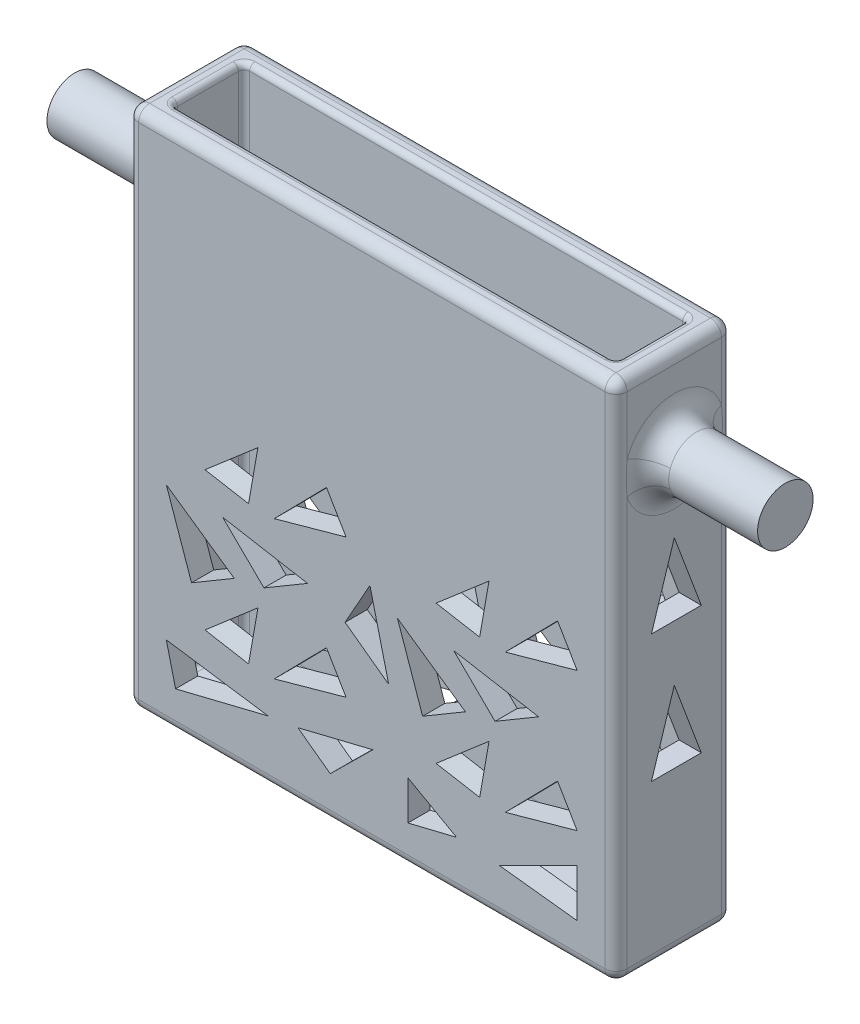
SolidWorks part; units mm, degrees
ref_plane "Front Plane" through (0, 0, 0) normal (0, 0, 1) x (1, 0, 0)
ref_plane "Top Plane" through (0, 0, 0) normal (0, 1, 0) x (1, 0, 0)
ref_plane "Right Plane" through (0, 0, 0) normal (1, 0, 0) x (0, 0, -1)
sketch "Sketch1" plane through (0, 0, 0) normal (0, 1, 0) x (1, 0, 0)
  line L0 (-40, 6.5) -> (-40, -6.5)
  line L1 (-38.5, 5) -> (38.5, 5) construction
  line L2 (-38.5, 5) -> (-38.5, -5) construction
  line L3 (-38.5, -5) -> (38.5, -5) construction
  line L4 (38.5, 5) -> (38.5, -5) construction
  line L5 (-38.5, 5) -> (38.5, -5) construction
  line L6 (-38.5, -5) -> (38.5, 5) construction
  line L7 (-40, -6.5) -> (40, -6.5)
  line L8 (40, 6.5) -> (40, -6.5)
  line L9 (-40, 6.5) -> (40, 6.5)
  line L10 (-44, 10.5) -> (44, 10.5)
  line L11 (44, 10.5) -> (44, -10.5)
  line L12 (-44, -10.5) -> (44, -10.5)
  line L13 (-44, 10.5) -> (-44, -10.5)
  point P0 (0, 0)
  dimension "D1" = 77
  dimension "D2" = 10
  dimension "D3" = 1.5
  dimension "D4" = 4
extrude "Boss-Extrude1" add sketch "Sketch1" along normal blind 90
sketch "Sketch2" plane through (0, 0, 0) normal (0, -1, 0) x (1, 0, 0)
  line L0 (44, 10.5) -> (44, -10.5) construction
  line L1 (44, -10.5) -> (-44, -10.5) construction
  line L2 (-44, 10.5) -> (44, 10.5) construction
  line L3 (-44, -10.5) -> (-44, 10.5) construction
  line L4 (44, 10.5) -> (44, -10.5)
  line L5 (44, -10.5) -> (-44, -10.5)
  line L6 (-44, 10.5) -> (44, 10.5)
  line L7 (-44, -10.5) -> (-44, 10.5)
extrude "Boss-Extrude2" add sketch "Sketch2" along normal blind 4
fillet "Fillet1" radius 1 12 edges at (0, 0, -6.5) (-40, 0, 0) (0, 0, 6.5) (40, 0, 0) (0, 90, -6.5) (-40, 90, 0) (0, 90, 6.5) (40, 90, 0) (40, 45, 6.5) (-40, 45, 6.5) (-40, 45, -6.5) (40, 45, -6.5)
fillet "Fillet2" radius 2 12 edges at (-44, -4, 0) (-44, 43, -10.5) (0, -4, -10.5) (44, 43, -10.5) (44, -4, 0) (44, 43, 10.5) (0, -4, 10.5) (-44, 43, 10.5) (0, 90, -10.5) (44, 90, 0) (0, 90, 10.5) (-44, 90, 0)
sketch "Sketch3" plane through (0, 0, 10.5) normal (0, 0, 1) x (1, 0, 0)
  line L90 (24.0616, 38.432) -> (33.4731, 48.0126)
  line L91 (33.4731, 48.0126) -> (37, 42.0321)
  line L92 (37, 42.0321) -> (24.0616, 38.432)
  line L93 (21.1238, 48.0459) -> (19.442, 38.4517)
  line L94 (11.591, 39.828) -> (21.1238, 48.0459)
  line L95 (19.442, 38.4517) -> (11.591, 39.828)
  line L96 (4.625, 34.0085) -> (9.1657, 20.9786)
  line L97 (16.8652, 25.5194) -> (4.625, 34.0085)
  line L98 (9.1657, 20.9786) -> (16.8652, 25.5194)
  line L99 (30.053, 31.3305) -> (14.7755, 34.0085)
  line L100 (22.2101, 26.7052) -> (30.053, 31.3305)
  line L101 (14.7755, 34.0085) -> (22.2101, 26.7052)
  line L102 (24.0616, 13.4362) -> (33.4731, 23.0168)
  line L103 (33.4731, 23.0168) -> (37, 17.0364)
  line L104 (37, 17.0364) -> (24.0616, 13.4362)
  line L105 (21.1238, 23.0502) -> (19.442, 13.456)
  line L106 (11.591, 14.8322) -> (21.1238, 23.0502)
  line L107 (19.442, 13.456) -> (11.591, 14.8322)
  line L114 (-17.5634, 38.432) -> (-8.1519, 48.0126)
  line L115 (-8.1519, 48.0126) -> (-4.625, 42.0321)
  line L116 (-4.625, 42.0321) -> (-17.5634, 38.432)
  line L117 (-20.5012, 48.0459) -> (-22.183, 38.4517)
  line L118 (-30.034, 39.828) -> (-20.5012, 48.0459)
  line L119 (-22.183, 38.4517) -> (-30.034, 39.828)
  line L120 (-37, 34.0085) -> (-32.4593, 20.9786)
  line L121 (-24.7598, 25.5194) -> (-37, 34.0085)
  line L122 (-32.4593, 20.9786) -> (-24.7598, 25.5194)
  line L123 (-11.572, 31.3305) -> (-26.8495, 34.0085)
  line L124 (-19.4149, 26.7052) -> (-11.572, 31.3305)
  line L125 (-26.8495, 34.0085) -> (-19.4149, 26.7052)
  line L126 (-17.5634, 13.4362) -> (-8.1519, 23.0168)
  line L127 (-8.1519, 23.0168) -> (-4.625, 17.0364)
  line L128 (-4.625, 17.0364) -> (-17.5634, 13.4362)
  line L129 (-20.5012, 23.0502) -> (-22.183, 13.456)
  line L130 (-30.034, 14.8322) -> (-20.5012, 23.0502)
  line L131 (-22.183, 13.456) -> (-30.034, 14.8322)
  line L135 (-0.3254, 36.6233) -> (-4.805, 28.6385)
  line L136 (-4.805, 28.6385) -> (3.0572, 22.8877)
  line L137 (3.0572, 22.8877) -> (-0.3254, 36.6233)
  line L138 (-37, 9.8118) -> (-18.6707, 7.1032)
  line L139 (-18.6707, 7.1032) -> (-35.3325, 3)
  line L140 (-35.3325, 3) -> (-37, 9.8118)
  line L141 (0.1885, 11.2606) -> (-13.3013, 7.9584)
  line L142 (-13.3013, 7.9584) -> (-7.4708, 3.6937)
  line L143 (-7.4708, 3.6937) -> (0.1885, 11.2606)
  line L144 (6.5166, 10.0557) -> (15.2728, 5.1434)
  line L145 (15.2728, 5.1434) -> (6.5166, 3)
  line L146 (6.5166, 3) -> (6.5166, 10.0557)
  line L147 (37, 11.588) -> (23.0287, 4.6007)
  line L148 (23.0287, 4.6007) -> (37, 3)
  line L149 (37, 3) -> (37, 11.588)
  line L152 (-42, -2) -> (42, -2) construction
  dimension "D5" = 5
extrude "Cut-Extrude1" cut sketch "Sketch3" against normal through all both and the other way through all
sketch "Sketch4" plane through (-44, 0, 0) normal (-1, 0, 0) x (0, 0, 1)
  line L4 (0, 60.9886) -> (-4.8622, 48.0227)
  line L5 (-4.8622, 48.0227) -> (4.1255, 48.0227)
  line L6 (4.1255, 48.0227) -> (0, 60.9886)
  line L7 (0, 37.9773) -> (-4.8622, 25.0114)
  line L8 (-4.8622, 25.0114) -> (4.1255, 25.0114)
  line L9 (4.1255, 25.0114) -> (0, 37.9773)
extrude "Cut-Extrude2" cut sketch "Sketch4" against normal through all both
sketch "Sketch5" plane through (-44, 0, 0) normal (-1, 0, 0) x (0, 0, 1)
  line L0 (0, 60.9886) -> (0, 88) construction
  line L1 (8.5, 88) -> (-8.5, 88) construction
  circle A0 centre (0, 74.4943) radius 5
  dimension "D1" = 10
extrude "Boss-Extrude3" add sketch "Sketch5" along normal blind 20
mirror "Mirror1" about plane through (0, 0, 0) normal (1, 0, 0) of "Boss-Extrude3"
fillet "Fillet3" radius 4 2 edges at (44, 74.4943, 5) (-44, 74.4943, -5)
sketch "Sketch6" plane through (-44, 0, 0) normal (-1, 0, 0) x (0, 0, 1)
  line L0 (8.5, -4) -> (-8.5, -4) construction
  circle A0 centre (0, 6) radius 3
  dimension "D1" = 6
  dimension "D2" = 10
extrude "Boss-Extrude4" add sketch "Sketch6" along normal blind 6
fillet "Fillet4" radius 2 1 edges at (-44, 6, -3)
